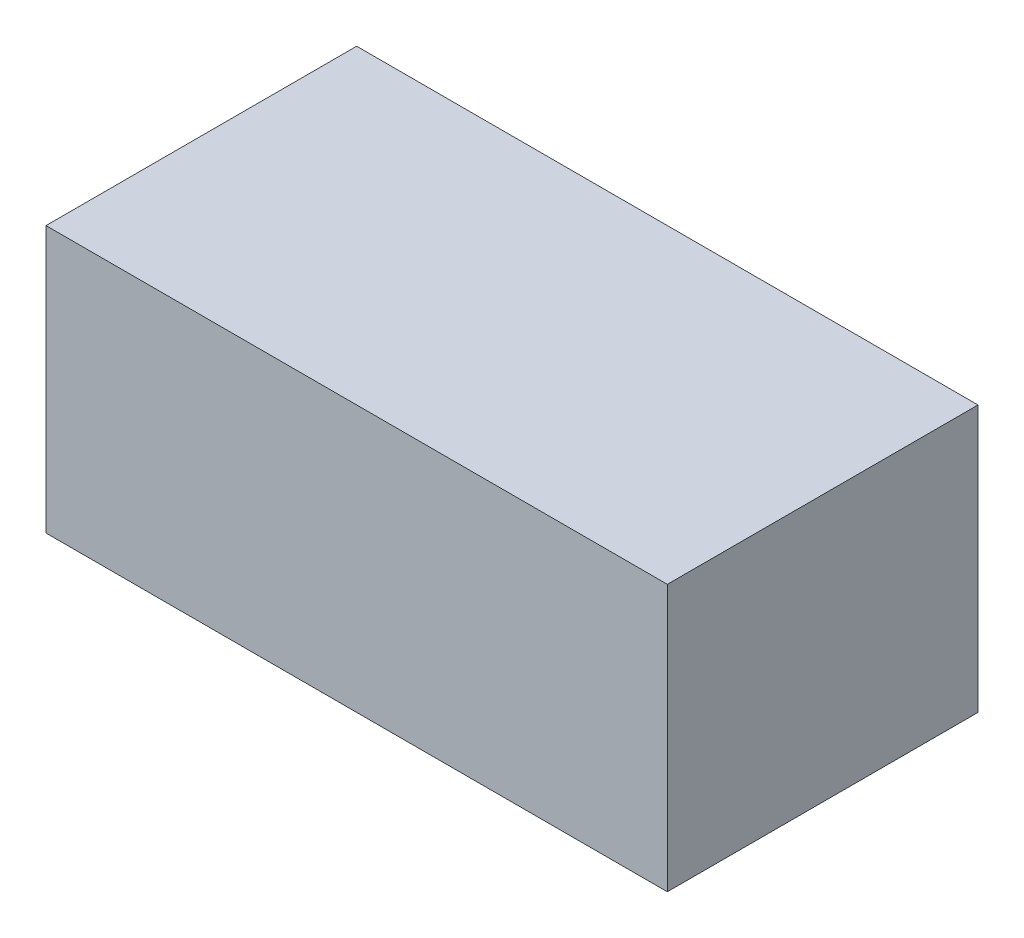
SolidWorks part; units mm, degrees
material "Copper"
ref_plane "Front Plane" through (0, 0, 0) normal (0, 0, 1) x (1, 0, 0)
ref_plane "Top Plane" through (0, 0, 0) normal (0, 1, 0) x (1, 0, 0)
ref_plane "Right Plane" through (0, 0, 0) normal (1, 0, 0) x (0, 0, -1)
sketch "Sketch1" plane through (0, 0, 0) normal (1, 0, 0) x (0, 0, -1)
  line L1 (0, 0) -> (35, 0)
  line L2 (0, 0) -> (0, 30)
  line L3 (0, 30) -> (35, 30)
  line L4 (35, 0) -> (35, 30)
  dimension "D1" = 30
  dimension "D2" = 35
extrude "Boss-Extrude1" add sketch "Sketch1" along normal blind 70
